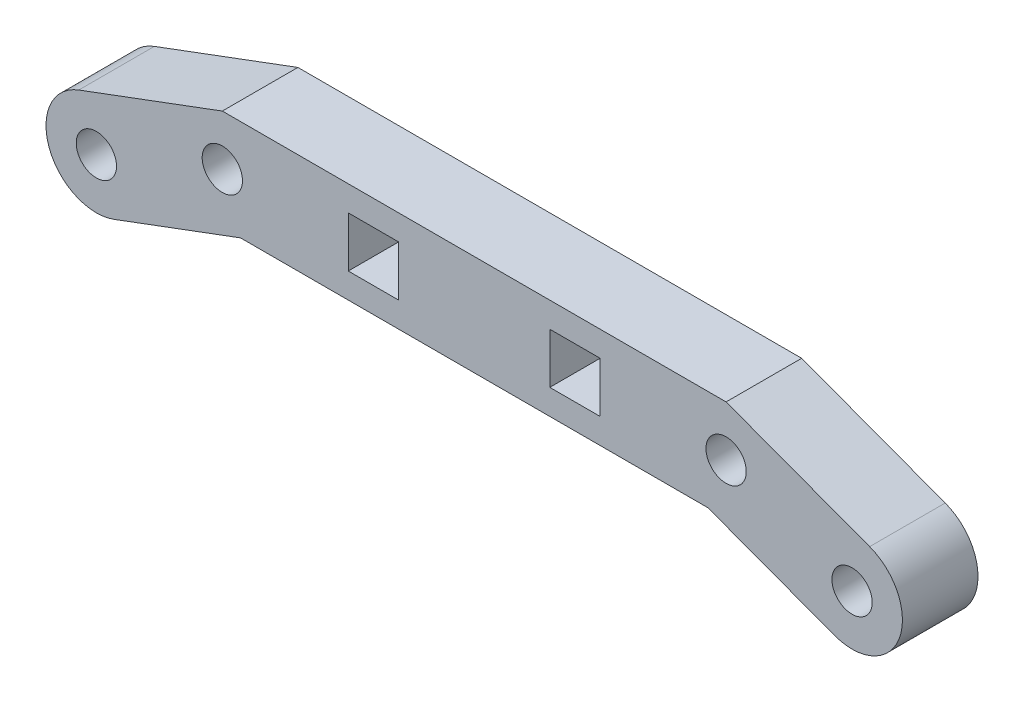
SolidWorks part; units mm, degrees
material "ABS"
ref_plane "Plano frontal" through (0, 0, 0) normal (0, 0, 1) x (1, 0, 0)
ref_plane "Plano superior" through (0, 0, 0) normal (0, 1, 0) x (1, 0, 0)
ref_plane "Plano direito" through (0, 0, 0) normal (1, 0, 0) x (0, 0, -1)
sketch "Esboço1" plane through (0, 0, 0) normal (0, 0, 1) x (1, 0, 0)
  line L0 (0, 0) -> (0, -20) construction
  line L1 (-25, -15) -> (-15, -5) construction
  line L2 (25, -5) -> (15, -5)
  line L3 (78.4954, -10.6308) -> (50, 0)
  line L4 (25, -5) -> (25, -15)
  line L5 (-46.3908, -20) -> (46.3908, -20)
  line L6 (25, -15) -> (15, -15)
  line L7 (15, -5) -> (15, -15)
  line L8 (25, -5) -> (15, -15) construction
  line L9 (25, -15) -> (15, -5) construction
  line L10 (-25, -5) -> (-15, -15) construction
  line L11 (-15, -5) -> (-15, -15)
  line L12 (-25, -15) -> (-15, -15)
  line L13 (-25, -5) -> (-25, -15)
  line L14 (-25, -5) -> (-15, -5)
  line L15 (50, 0) -> (0, 0)
  line L16 (0, 0) -> (-50, 0)
  line L17 (-50, 0) -> (-78.4954, -10.6308)
  line L18 (-71.5046, -29.3692) -> (-46.3908, -20)
  line L20 (46.3908, -20) -> (71.5046, -29.3692)
  circle A0 centre (-50, -10) radius 4
  circle A1 centre (50, -10) radius 4
  arc A4 (-78.4954, -10.6308) -> (-71.5046, -29.3692) centre (-75, -20) ccw
  arc A5 (78.4954, -10.6308) -> (71.5046, -29.3692) centre (75, -20) cw
  circle A6 centre (-75, -20) radius 4
  circle A7 centre (75, -20) radius 4
  point P0 (0, 0)
  point P1 (20, -10)
  point P13 (63, -13)
  point P15 (-42.9224, -19.6491)
  point P24 (-20, -10)
  point P29 (-40.8894, -18)
  point P33 (0, 0)
  point P34 (0, -20)
  point P35 (0, -10)
  point P36 (50, 0)
  point P37 (0, 0)
  point P38 (48.8489, 0)
  point P39 (0, 0)
  dimension "D3" = 8
  dimension "D4" = 100
  dimension "D2" = 10
  dimension "D8" = 10
  dimension "D12" = 8
  dimension "D7" = 40
  dimension "D5" = 20
  dimension "D6" = 10
  dimension "D13" = 150
extrude "Ressalto-extrusão1" add sketch "Esboço1" along normal blind 15
